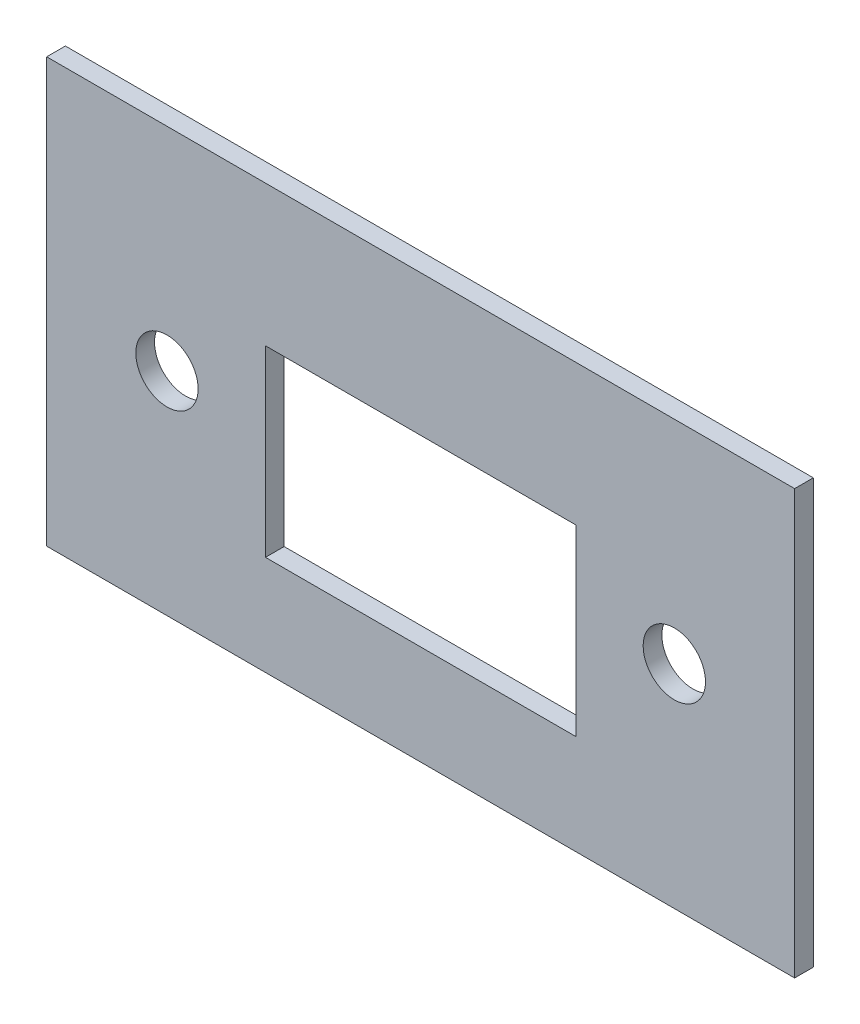
SolidWorks part; units mm, degrees
ref_plane "Front Plane" through (0, 0, 0) normal (0, 0, 1) x (1, 0, 0)
ref_plane "Top Plane" through (0, 0, 0) normal (0, 1, 0) x (1, 0, 0)
ref_plane "Right Plane" through (0, 0, 0) normal (1, 0, 0) x (0, 0, -1)
sketch "Esquisse2" plane through (0, 0, 0) normal (0, 0, 1) x (1, 0, 0)
  line L0 (0, 1.5) -> (0, 29.8) construction
  line L4 (26.4, 28.3) -> (-26.4, 28.3)
  line L5 (-26.4, 28.3) -> (-26.4, 1.5)
  line L6 (-26.4, 1.5) -> (26.4, 1.5)
  line L7 (26.4, 1.5) -> (26.4, 28.3)
  line L12 (-27.9, 29.8) -> (-27.9, 0)
  line L13 (-27.9, 0) -> (27.9, 0)
  line L14 (27.9, 0) -> (27.9, 29.8)
  line L15 (27.9, 29.8) -> (-27.9, 29.8)
  point P7 (0, 0)
  point P9 (0, 0)
  point P13 (0, 42.073)
  point P14 (0, 30)
  dimension "D1" = 55.8
  dimension "D3" = 29.8
  dimension "D2" = 1.5
extrude "Boss.-Extru.1" add sketch "Esquisse2" against normal blind 2
sketch "Esquisse3" plane through (0, 0, 0) normal (0, 0, 1) x (1, 0, 0)
  line L0 (-26.4, 14.9) -> (26.4, 14.9) construction
  line L1 (-26.4, 28.3) -> (-26.4, 1.5) construction
  line L2 (26.4, 1.5) -> (26.4, 28.3) construction
  line L8 (30, -2.1) -> (30, 31.9)
  line L9 (30, 31.9) -> (-30, 31.9)
  line L10 (-30, 31.9) -> (-30, -2.1)
  line L11 (-30, -2.1) -> (30, -2.1)
  dimension "D1" = 34
extrude "Boss.-Extru.2" add sketch "Esquisse3" along normal blind 1.5
sketch "Esquisse4" plane through (0, 0, 1.5) normal (0, 0, 1) x (1, 0, 0)
  line L8 (0, 31.9) -> (0, -2.1) construction
  line L9 (30, 31.9) -> (-30, 31.9) construction
  line L10 (-30, -2.1) -> (30, -2.1) construction
  line L12 (12.45, 20.6) -> (-12.45, 20.6)
  line L13 (-12.45, 20.6) -> (-12.45, 5.9)
  line L14 (-12.45, 5.9) -> (12.45, 5.9)
  line L15 (12.45, 5.9) -> (12.45, 20.6)
  point P7 (0, 20.6)
  point P9 (12.45, 20.7)
  dimension "D1" = 8
  dimension "D2" = 14.7
  dimension "D3" = 24.9
extrude "Enlèv. mat.-Extru.1" cut sketch "Esquisse4" against normal up to surface (1.5 mm away) up to face at (0, 14.9, 0)
sketch "Esquisse5" plane through (0, 0, 0) normal (0, 0, -1) x (-1, 0, 0)
  circle A0 centre (20.35, 14.9) radius 2.5
  circle A1 centre (-20.35, 14.9) radius 2.5
  dimension "D1" = 5
extrude "Enlèv. mat.-Extru.2" cut sketch "Esquisse5" against normal up to surface (1.5 mm away) up to face at (0, 13.25, 1.5)
